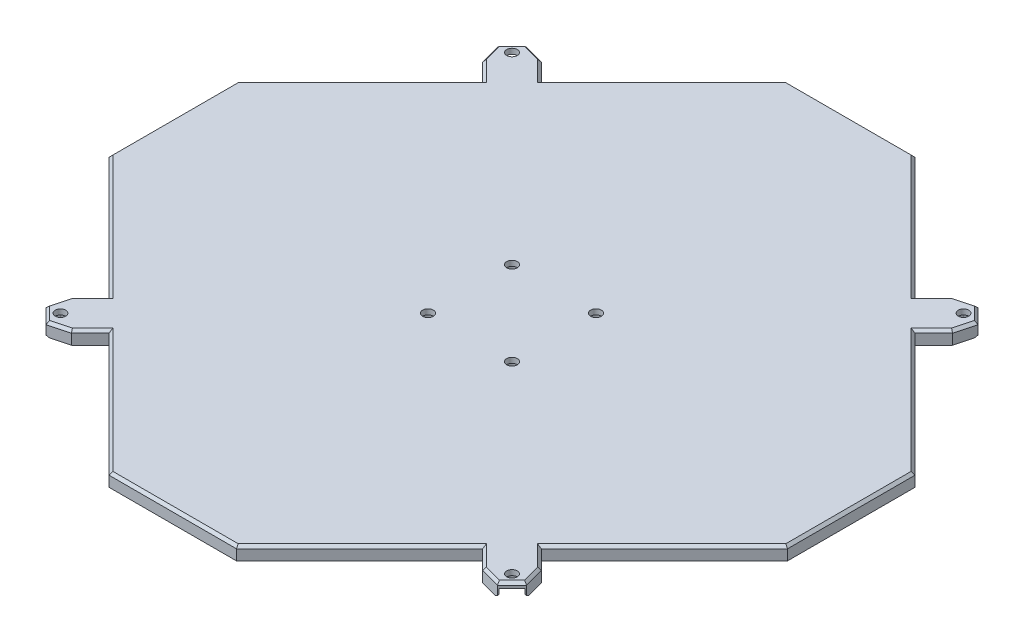
SolidWorks part; units mm, degrees
material "ABS"
ref_plane "Front Plane" through (0, 0, 0) normal (0, 0, 1) x (1, 0, 0)
ref_plane "Top Plane" through (0, 0, 0) normal (0, 1, 0) x (1, 0, 0)
ref_plane "Right Plane" through (0, 0, 0) normal (1, 0, 0) x (0, 0, -1)
sketch "Floor Reference" plane through (0, 0, 0) normal (0, 1, 0) x (-1, 0, 0)
  line L0 (-129.3223, 24.3223) -> (-82.4792, 71.1655)
  line L1 (-82.4792, 71.1655) -> (-89.601, 78.2873)
  line L2 (-89.601, 78.2873) -> (-91.6716, 86.0147)
  line L3 (-91.6716, 86.0147) -> (-86.0147, 91.6716)
  line L4 (-86.0147, 91.6716) -> (-78.2873, 89.601)
  line L5 (-78.2873, 89.601) -> (-71.1655, 82.4792)
  line L6 (-71.1655, 82.4792) -> (-24.3223, 129.3223)
  line L7 (-24.3223, 129.3223) -> (0, 129.3223)
  line L31 (-129.3223, 0) -> (-129.3223, 24.3223)
  line L32 (0, 0) -> (-35355.3391, 35355.3391) construction
  line L34 (-1000, 0) -> (0, 0) construction
  line L35 (0, 0) -> (0, 49000) construction
  circle A0 centre (-86.0147, 86.0147) radius 2
  point P18 (-88.8431, 88.8431)
  dimension "D11" = 4
  dimension "D1" = 105
  dimension "D2" = 45
  dimension "D3" = 129.3223
  dimension "D4" = 8
  dimension "D5" = 16
  dimension "D6" = 17
  dimension "D7" = 8
  dimension "D8" = 13
  dimension "D9" = 105
  dimension "D10" = 24.3223
sketch "Sketch2" plane through (0, 0, 0) normal (0, 1, 0) x (1, 0, 0)
  line L0 (129.3223, 0) -> (129.3223, -24.3223) construction
  line L1 (129.3223, -24.3223) -> (82.4792, -71.1655) construction
  line L2 (82.4792, -71.1655) -> (89.601, -78.2873) construction
  line L3 (89.601, -78.2873) -> (91.6716, -86.0147) construction
  line L4 (91.6716, -86.0147) -> (86.0147, -91.6716) construction
  line L5 (86.0147, -91.6716) -> (78.2873, -89.601) construction
  line L6 (78.2873, -89.601) -> (71.1655, -82.4792) construction
  line L7 (71.1655, -82.4792) -> (24.3223, -129.3223) construction
  line L8 (24.3223, -129.3223) -> (0, -129.3223) construction
  line L9 (129.3223, 0) -> (129.3223, -24.3223) construction
  line L10 (129.3223, -24.3223) -> (82.4792, -71.1655) construction
  line L11 (82.4792, -71.1655) -> (89.601, -78.2873) construction
  line L12 (89.601, -78.2873) -> (91.6716, -86.0147) construction
  line L13 (91.6716, -86.0147) -> (86.0147, -91.6716) construction
  line L14 (86.0147, -91.6716) -> (78.2873, -89.601) construction
  line L15 (78.2873, -89.601) -> (71.1655, -82.4792) construction
  line L16 (71.1655, -82.4792) -> (24.3223, -129.3223) construction
  line L17 (24.3223, -129.3223) -> (0, -129.3223) construction
  line L18 (-129.3223, -24.3223) -> (-129.3223, 0) construction
  line L19 (-82.4792, -71.1655) -> (-129.3223, -24.3223) construction
  line L20 (-89.601, -78.2873) -> (-82.4792, -71.1655) construction
  line L21 (-91.6716, -86.0147) -> (-89.601, -78.2873) construction
  line L22 (-86.0147, -91.6716) -> (-91.6716, -86.0147) construction
  line L23 (-78.2873, -89.601) -> (-86.0147, -91.6716) construction
  line L24 (-71.1655, -82.4792) -> (-78.2873, -89.601) construction
  line L25 (-24.3223, -129.3223) -> (-71.1655, -82.4792) construction
  line L26 (0, -129.3223) -> (-24.3223, -129.3223) construction
  line L27 (-24.3223, 129.3223) -> (0, 129.3223) construction
  line L28 (-71.1655, 82.4792) -> (-24.3223, 129.3223) construction
  line L29 (-78.2873, 89.601) -> (-71.1655, 82.4792) construction
  line L30 (-86.0147, 91.6716) -> (-78.2873, 89.601) construction
  line L31 (-91.6716, 86.0147) -> (-86.0147, 91.6716) construction
  line L32 (-89.601, 78.2873) -> (-91.6716, 86.0147) construction
  line L33 (-82.4792, 71.1655) -> (-89.601, 78.2873) construction
  line L34 (-129.3223, 24.3223) -> (-82.4792, 71.1655) construction
  line L35 (-129.3223, 0) -> (-129.3223, 24.3223) construction
  line L36 (129.3223, 24.3223) -> (129.3223, 0) construction
  line L37 (82.4792, 71.1655) -> (129.3223, 24.3223) construction
  line L38 (89.601, 78.2873) -> (82.4792, 71.1655) construction
  line L39 (91.6716, 86.0147) -> (89.601, 78.2873) construction
  line L40 (86.0147, 91.6716) -> (91.6716, 86.0147) construction
  line L41 (78.2873, 89.601) -> (86.0147, 91.6716) construction
  line L42 (71.1655, 82.4792) -> (78.2873, 89.601) construction
  line L43 (24.3223, 129.3223) -> (71.1655, 82.4792) construction
  line L44 (0, 129.3223) -> (24.3223, 129.3223) construction
  line L45 (129.2223, 0) -> (129.2223, -24.2809)
  line L46 (129.2223, -24.2809) -> (82.3378, -71.1655)
  line L47 (82.3378, -71.1655) -> (89.5114, -78.3391)
  line L48 (89.5114, -78.3391) -> (91.56, -85.9848)
  line L49 (91.56, -85.9848) -> (85.9848, -91.56)
  line L50 (85.9848, -91.56) -> (78.3391, -89.5114)
  line L51 (78.3391, -89.5114) -> (71.1655, -82.3378)
  line L52 (71.1655, -82.3378) -> (24.2809, -129.2223)
  line L53 (24.2809, -129.2223) -> (0, -129.2223)
  line L54 (0, -129.2223) -> (-24.2809, -129.2223)
  line L55 (-24.2809, -129.2223) -> (-71.1655, -82.3378)
  line L56 (-71.1655, -82.3378) -> (-78.3391, -89.5114)
  line L57 (-78.3391, -89.5114) -> (-85.9848, -91.56)
  line L58 (-85.9848, -91.56) -> (-91.56, -85.9848)
  line L59 (-91.56, -85.9848) -> (-89.5114, -78.3391)
  line L60 (-89.5114, -78.3391) -> (-82.3378, -71.1655)
  line L61 (-82.3378, -71.1655) -> (-129.2223, -24.2809)
  line L62 (-129.2223, -24.2809) -> (-129.2223, 0)
  line L63 (-129.2223, 0) -> (-129.2223, 24.2809)
  line L64 (-129.2223, 24.2809) -> (-82.3378, 71.1655)
  line L65 (-82.3378, 71.1655) -> (-89.5114, 78.3391)
  line L66 (-89.5114, 78.3391) -> (-91.56, 85.9848)
  line L67 (-91.56, 85.9848) -> (-85.9848, 91.56)
  line L68 (-85.9848, 91.56) -> (-78.3391, 89.5114)
  line L69 (-78.3391, 89.5114) -> (-71.1655, 82.3378)
  line L70 (-71.1655, 82.3378) -> (-24.2809, 129.2223)
  line L71 (-24.2809, 129.2223) -> (0, 129.2223)
  line L72 (0, 129.2223) -> (24.2809, 129.2223)
  line L73 (24.2809, 129.2223) -> (71.1655, 82.3378)
  line L74 (71.1655, 82.3378) -> (78.3391, 89.5114)
  line L75 (78.3391, 89.5114) -> (85.9848, 91.56)
  line L76 (85.9848, 91.56) -> (91.56, 85.9848)
  line L77 (91.56, 85.9848) -> (89.5114, 78.3391)
  line L78 (89.5114, 78.3391) -> (82.3378, 71.1655)
  line L79 (82.3378, 71.1655) -> (129.2223, 24.2809)
  line L80 (129.2223, 24.2809) -> (129.2223, 0)
  circle A0 centre (86.0147, -86.0147) radius 2 construction
  circle A1 centre (86.0147, -86.0147) radius 2
  circle A2 centre (-86.0147, -86.0147) radius 2
  circle A3 centre (-86.0147, 86.0147) radius 2
  circle A4 centre (86.0147, 86.0147) radius 2
  point P13 (0, 0)
  point P54 (0, 0)
  dimension "D2" = 0.1
  dimension "D1" = 4
extrude "Main Floor Extrude" add sketch "Sketch2" along normal blind 5
chamfer "Main Floor Chamfer" distance 1 angle 45 32 edges at (-74.7523, 5, -85.9246) (-82.162, 5, -90.5357) (-88.7724, 5, -88.7724) (-90.5357, 5, -82.162) (-85.9246, 5, -74.7523) (-47.7232, 5, -105.78) (0, 5, -129.2223) (47.7232, 5, -105.78) (74.7523, 5, -85.9246) (82.162, 5, -90.5357) (88.7724, 5, -88.7724) (90.5357, 5, -82.162) (85.9246, 5, -74.7523) (105.78, 5, -47.7232) (129.2223, 5, 0) (105.78, 5, 47.7232) (85.9246, 5, 74.7523) (90.5357, 5, 82.162) (88.7724, 5, 88.7724) (82.162, 5, 90.5357) (74.7523, 5, 85.9246) (47.7232, 5, 105.78) (0, 5, 129.2223) (-47.7232, 5, 105.78) (-74.7523, 5, 85.9246) (-82.162, 5, 90.5357) (-88.7724, 5, 88.7724) (-90.5357, 5, 82.162) (-85.9246, 5, 74.7523) (-105.78, 5, 47.7232) (-129.2223, 5, 0) (-105.78, 5, -47.7232)
sketch "Sketch3" plane through (0, 0, 0) normal (0, -1, 0) x (-1, 0, 0)
  line L0 (91.2473, -86.2976) -> (88.4896, -83.5398)
  line L1 (91.56, -85.9848) -> (85.9848, -91.56) construction
  line L2 (83.5398, -88.4896) -> (86.2976, -91.2473)
  line L3 (86.2976, -91.2473) -> (91.2473, -86.2976)
  line L4 (-86.2976, -91.2473) -> (-83.5398, -88.4896)
  line L5 (-88.4896, -83.5398) -> (-91.2473, -86.2976)
  line L6 (-91.2473, -86.2976) -> (-86.2976, -91.2473)
  line L7 (-91.2473, 86.2976) -> (-88.4896, 83.5398)
  line L8 (-83.5398, 88.4896) -> (-86.2976, 91.2473)
  line L9 (-86.2976, 91.2473) -> (-91.2473, 86.2976)
  line L10 (86.2976, 91.2473) -> (83.5398, 88.4896)
  line L11 (88.4896, 83.5398) -> (91.2473, 86.2976)
  line L12 (91.2473, 86.2976) -> (86.2976, 91.2473)
  arc A0 (88.4896, -83.5398) -> (83.5398, -88.4896) centre (86.0147, -86.0147) ccw
  arc A1 (83.5398, -88.4896) -> (88.4896, -83.5398) centre (86.0147, -86.0147) ccw construction
  arc A2 (-83.5398, -88.4896) -> (-88.4896, -83.5398) centre (-86.0147, -86.0147) ccw
  arc A3 (-88.4896, -83.5398) -> (-83.5398, -88.4896) centre (-86.0147, -86.0147) ccw construction
  arc A4 (-88.4896, 83.5398) -> (-83.5398, 88.4896) centre (-86.0147, 86.0147) ccw
  arc A5 (-83.5398, 88.4896) -> (-88.4896, 83.5398) centre (-86.0147, 86.0147) ccw construction
  arc A6 (83.5398, 88.4896) -> (88.4896, 83.5398) centre (86.0147, 86.0147) ccw
  arc A7 (88.4896, 83.5398) -> (83.5398, 88.4896) centre (86.0147, 86.0147) ccw construction
  point P1 (0, 0)
  point P28 (0, 0)
  dimension "D1" = 7
  dimension "D2" = 4
extrude "Mount Screw Countersink" cut sketch "Sketch3" against normal blind 3
chamfer "Mount Screw Countersink Chamfer" distance 1 angle 45 12 edges at (-84.9187, 0, -89.8685) (-89.8685, 0, -84.9187) (-83.5398, 0, -83.5398) (89.8685, 0, -84.9187) (84.9187, 0, -89.8685) (83.5398, 0, -83.5398) (84.9187, 0, 89.8685) (89.8685, 0, 84.9187) (83.5398, 0, 83.5398) (-89.8685, 0, 84.9187) (-84.9187, 0, 89.8685) (-83.5398, 0, 83.5398)
sketch "Sketch6" plane through (0, 5, 0) normal (0, 1, 0) x (1, 0, 0)
  line L1 (-16, -16) -> (16, -16) construction
  line L2 (-16, -16) -> (-16, 16) construction
  line L3 (-16, 16) -> (16, 16) construction
  line L4 (16, -16) -> (16, 16) construction
  line L5 (-16, -16) -> (16, 16) construction
  line L6 (-16, 16) -> (16, -16) construction
  circle A0 centre (-16, 16) radius 2.05
  circle A1 centre (16, 16) radius 2.05
  circle A2 centre (16, -16) radius 2.05
  circle A3 centre (-16, -16) radius 2.05
  point P0 (0, 0)
  dimension "D2" = 4.1
  dimension "D1" = 32
extrude "Bottom Motor Mount Holes" cut sketch "Sketch6" against normal through all
sketch "Sketch7" plane through (0, 0, 0) normal (0, -1, 0) x (-1, 0, 0)
  circle A0 centre (16, -16) radius 3.5
  circle A1 centre (-16, -16) radius 3.5
  circle A2 centre (-16, 16) radius 3.5
  circle A3 centre (16, 16) radius 3.5
  dimension "D1" = 7
extrude "Bottom Motor Mount Holes Countersink" cut sketch "Sketch7" against normal blind 3
